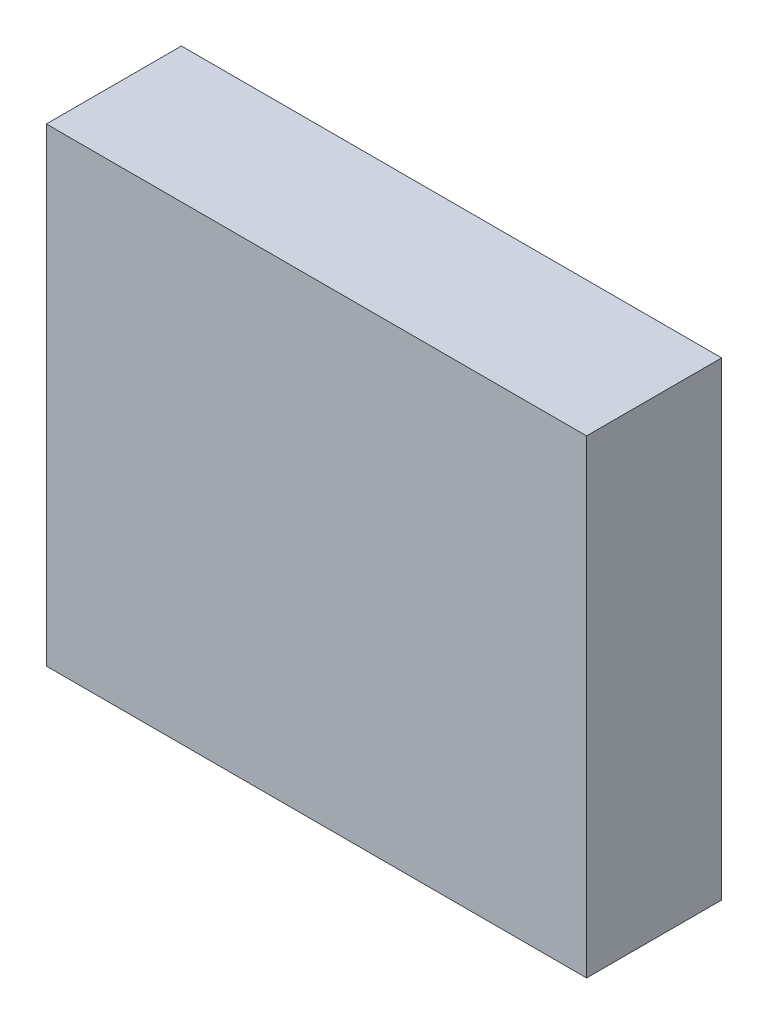
SolidWorks part; units mm, degrees
ref_plane "前视基准面" through (0, 0, 0) normal (0, 0, 1) x (1, 0, 0)
ref_plane "上视基准面" through (0, 0, 0) normal (0, 1, 0) x (1, 0, 0)
ref_plane "右视基准面" through (0, 0, 0) normal (1, 0, 0) x (0, 0, -1)
other "Configuration Table"
sketch "草图1" plane through (0, 0, 0) normal (0, 0, 1) x (1, 0, 0)
  line L1 (-42, 36.5) -> (42, 36.5)
  line L2 (-42, 36.5) -> (-42, -36.5)
  line L3 (-42, -36.5) -> (42, -36.5)
  line L4 (42, 36.5) -> (42, -36.5)
  line L5 (-42, 36.5) -> (42, -36.5) construction
  line L6 (-42, -36.5) -> (42, 36.5) construction
  point P0 (0, 0)
  dimension "D1" = 73
  dimension "D2" = 84
extrude "凸台-拉伸1" add sketch "草图1" along normal blind 21
